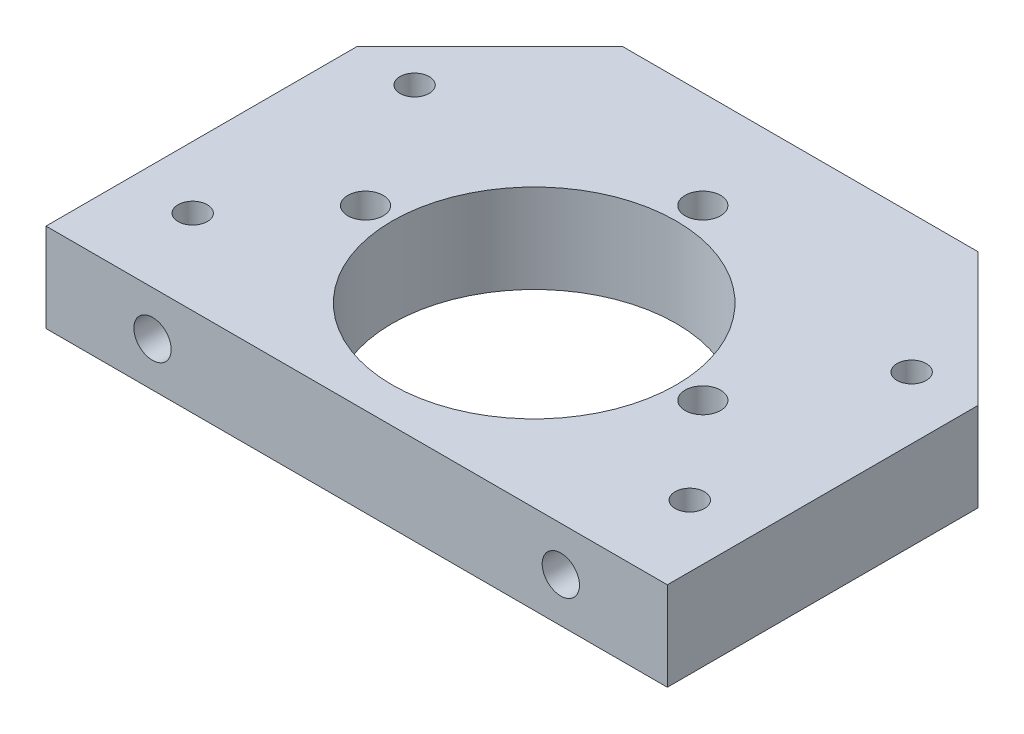
SolidWorks part; units mm, degrees
ref_plane "Спереди" through (0, 0, 0) normal (0, 0, 1) x (1, 0, 0)
ref_plane "Сверху" through (0, 0, 0) normal (0, 1, 0) x (1, 0, 0)
ref_plane "Справа" through (0, 0, 0) normal (1, 0, 0) x (0, 0, -1)
sketch "Эскиз1" plane through (0, 0, 0) normal (0, 1, 0) x (1, 0, 0)
  line L0 (13.1228, 23.7562) -> (13.1228, -26.2438) construction
  line L1 (-21.8772, 23.7562) -> (48.1228, 23.7562)
  line L2 (-21.8772, 23.7562) -> (-21.8772, -26.2438)
  line L3 (-21.8772, -26.2438) -> (48.1228, -26.2438)
  line L4 (48.1228, 23.7562) -> (48.1228, -26.2438)
  circle A0 centre (13.1228, -6.2438) radius 16
  dimension "D3" = 20
  dimension "D4" = 32
  dimension "D1" = 70
  dimension "D2" = 50
extrude "Бобышка-Вытянуть1" add sketch "Эскиз1" along normal blind 10
chamfer "Фаска1" distance 15 angle 45 2 edges at (48.1228, 5, -23.7562) (-21.8772, 5, -23.7562)
sketch "Эскиз4" plane through (0, 10, 0) normal (0, 1, 0) x (1, 0, 0)
  circle A0 centre (32.1228, -6.2438) radius 2
  circle A1 centre (13.1228, 12.7562) radius 2
  circle A2 centre (-5.8772, -6.2438) radius 2
  circle A3 centre (13.1228, -6.2438) radius 19 construction
  dimension "D1" = 4
  dimension "D2" = 4
  dimension "D3" = 4
extrude "Вырез-Вытянуть3" cut sketch "Эскиз4" against normal blind 10
sketch "Эскиз7" plane through (0, 10, 0) normal (0, 1, 0) x (1, 0, 0)
  circle A0 centre (41.1228, 8.2812) radius 1.65
  circle A1 centre (41.1228, -16.7188) radius 1.65
  circle A2 centre (-14.8772, 8.2812) radius 1.65
  circle A3 centre (-14.8772, -16.7188) radius 1.65
  dimension "D1" = 3.3
  dimension "D2" = 3.3
  dimension "D3" = 3.3
  dimension "D4" = 3.3
extrude "Вырез-Вытянуть5" cut sketch "Эскиз7" against normal blind 10
sketch "Эскиз8" plane through (0, 0, 26.2438) normal (0, 0, 1) x (1, 0, 0)
  line L0 (-21.8772, 5) -> (48.1228, 5) construction
  line L1 (-21.8772, 10) -> (-21.8772, 0) construction
  line L2 (48.1228, 10) -> (48.1228, 0) construction
  line L4 (-21.8772, 10) -> (48.1228, 10) construction
  line L5 (13.1228, 10) -> (13.1228, 0) construction
  line L6 (-21.8772, 0) -> (48.1228, 0) construction
  circle A0 centre (-9.8772, 5) radius 2.1
  circle A1 centre (36.1228, 5) radius 2.1
  dimension "D1" = 46
  dimension "D2" = 23
  dimension "D3" = 4.2
  dimension "D4" = 4.2
extrude "Вырез-Вытянуть6" cut sketch "Эскиз8" against normal blind 15
